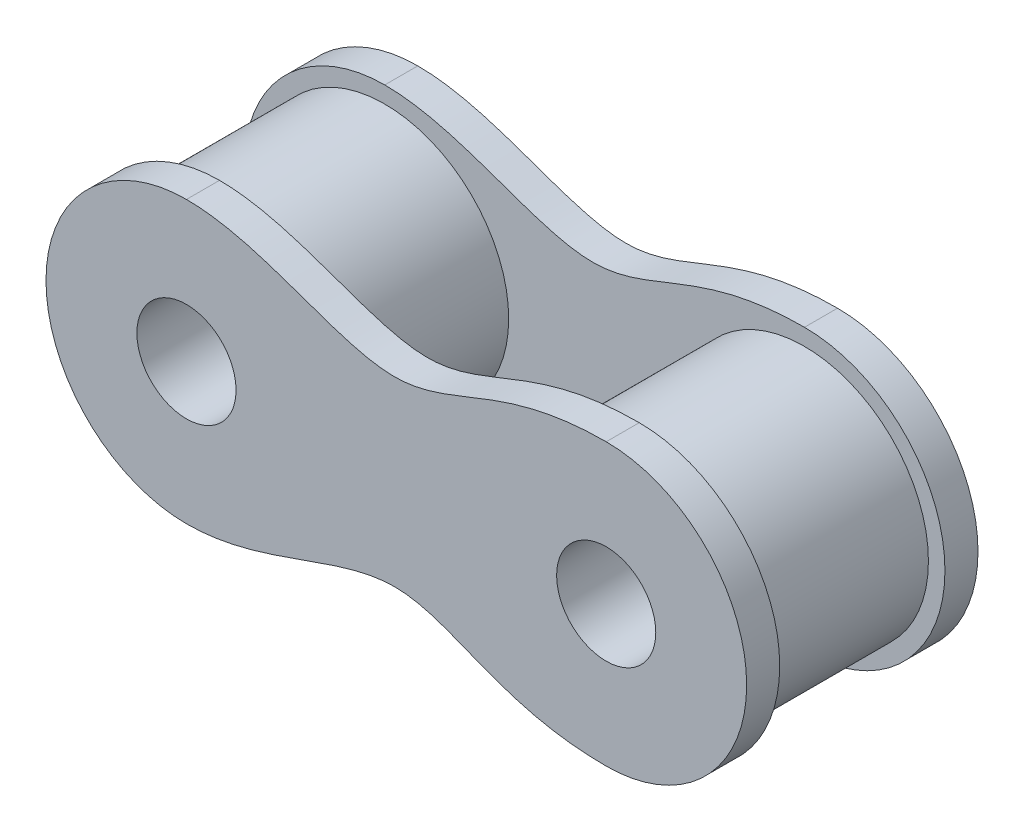
SolidWorks part; units mm, degrees
ref_plane "Front Plane" through (0, 0, 0) normal (0, 0, 1) x (1, 0, 0)
ref_plane "Top Plane" through (0, 0, 0) normal (0, 1, 0) x (1, 0, 0)
ref_plane "Right Plane" through (0, 0, 0) normal (1, 0, 0) x (0, 0, -1)
sketch "Sketch1" plane through (0, 0, 0) normal (0, 0, 1) x (1, 0, 0)
  circle A0 centre (0, 0) radius 3.75
  circle A1 centre (0, 0) radius 1.5
  circle A2 centre (12.7, 0) radius 1.5
  circle A3 centre (12.7, 0) radius 3.75
  dimension "D1" = 7.5
  dimension "D2" = 3
  dimension "D3" = 3
  dimension "D4" = 7.5
  dimension "D5" = 12.7
extrude "Boss-Extrude1" add sketch "Sketch1" along normal blind 5
sketch "Sketch3" plane through (0, 0, 5) normal (0, 0, 1) x (1, 0, 0)
  line L0 (0, 5.9523) -> (0, -5.9751) construction
  line L1 (-6.9002, 0) -> (19.4405, 0) construction
  line L2 (12.7, 5.9523) -> (12.7, -6.2488) construction
  arc A0 (0, 4.25) -> (0, -4.25) centre (0, 0) ccw
  arc A1 (12.7, -4.25) -> (12.7, 4.25) centre (12.7, 0) ccw
  circle A2 centre (12.7, 0) radius 1.5 construction
  circle A3 centre (0, 0) radius 1.5 construction
  circle A4 centre (12.7, 0) radius 1.5
  circle A5 centre (0, 0) radius 1.5
  spline S0 degree 3 poles (0, 4.25) (2.289, 4.25) (6.7577, 1.2493) (9.4084, 4.25) (12.7, 4.25) knots 0 0 0 0 0.492542 1 1 1 1
  spline S1 degree 3 poles (0, -4.25) (2.289, -4.25) (6.7577, -1.2493) (9.4084, -4.25) (12.7, -4.25) knots 0 0 0 0 0.492542 1 1 1 1
  dimension "D1" = 8.5
  dimension "D2" = 8.5
  dimension "D3" = 6.25
  dimension "D4" = 1.5
extrude "Boss-Extrude2" add sketch "Sketch3" along normal blind 1
sketch "Sketch4" plane through (0, 0, 0) normal (0, 0, -1) x (-1, 0, 0)
  circle A0 centre (0, 0) radius 1.5 construction
  circle A1 centre (-12.7, 0) radius 1.5 construction
  arc A2 (0, -4.25) -> (0, 4.25) centre (0, 0) ccw construction
  arc A3 (-12.7, 4.25) -> (-12.7, -4.25) centre (-12.7, 0) ccw construction
  circle A4 centre (0, 0) radius 1.5
  circle A5 centre (-12.7, 0) radius 1.5
  arc A6 (0, -4.25) -> (0, 4.25) centre (0, 0) ccw
  arc A7 (-12.7, 4.25) -> (-12.7, -4.25) centre (-12.7, 0) ccw
  spline S0 degree 3 poles (-127.7559, 1991.0737) (64.8421, -129.573) (-40.4204, 114.118) (-3.839, -110.4431) (-1365.5988, 1467.8328) knots -4.097012 -4.097012 -4.097012 -4.097012 0.492542 4.736143 4.736143 4.736143 4.736143 only from (0, -4.25) to (-12.7, -4.25) construction
  spline S1 degree 3 poles (-1365.5783, -1467.8091) (-3.8392, 110.442) (-40.4202, -114.1174) (64.8422, 129.5731) (-127.756, -1991.0755) knots -3.736122 -3.736122 -3.736122 -3.736122 0.507458 5.097014 5.097014 5.097014 5.097014 only from (-12.7, 4.25) to (0, 4.25) construction
  spline S2 degree 3 poles (0, -4.25) (-2.289, -4.25) (-6.7577, -1.2493) (-9.4084, -4.25) (-12.7, -4.25) knots 0 0 0 0 0.492542 1 1 1 1
  spline S3 degree 3 poles (-12.7, 4.25) (-9.4084, 4.25) (-6.7577, 1.2493) (-2.289, 4.25) (0, 4.25) knots 0 0 0 0 0.507458 1 1 1 1
extrude "Boss-Extrude3" add sketch "Sketch4" along normal blind 1
ref_plane "Plane1" through (0, 0, 2.5) normal (0, 0, 1) x (1, 0, 0)
